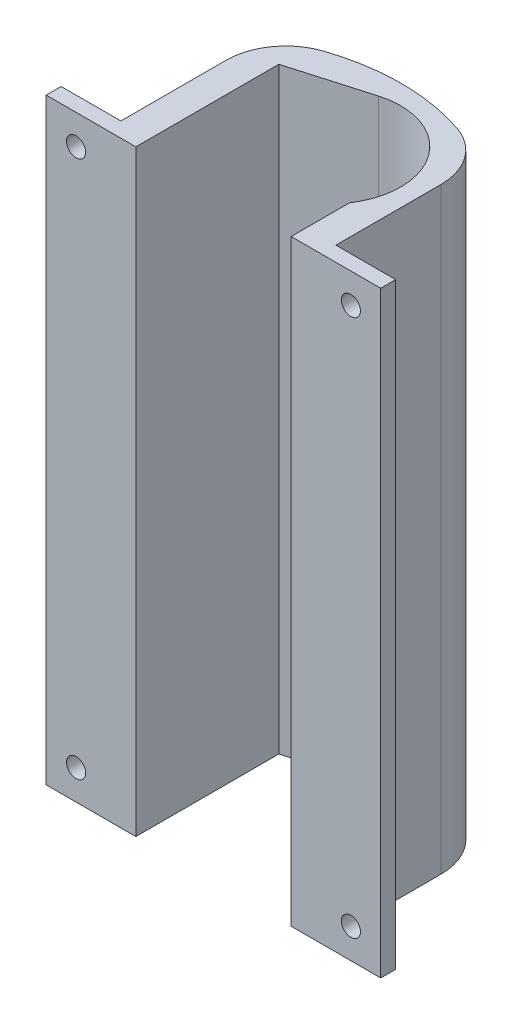
SolidWorks part; units mm, degrees
ref_plane "Front Plane" through (0, 0, 0) normal (0, 0, 1) x (1, 0, 0)
ref_plane "Top Plane" through (0, 0, 0) normal (0, 1, 0) x (1, 0, 0)
ref_plane "Right Plane" through (0, 0, 0) normal (1, 0, 0) x (0, 0, -1)
sketch "Sketch1" plane through (0, 0, 0) normal (0, 1, 0) x (1, 0, 0)
  line L0 (-20.574, -9.6521) -> (-4.162, -14.3967) construction
  line L1 (-4.1621, 14.3967) -> (-20.574, 9.652) construction
  line L2 (-20.574, 9.652) -> (-20.574, -9.6521) construction
  line L3 (-39.624, 20.7467) -> (-20.574, 20.7467) construction
  line L4 (-39.624, 20.7467) -> (-39.624, 17.5717) construction
  line L6 (12.446, 20.7467) -> (31.496, 20.7467) construction
  line L7 (-39.624, 17.5717) -> (-26.924, 17.5717) construction
  line L9 (-26.924, 17.5717) -> (-26.924, -12.8271) construction
  line L10 (31.496, 20.7467) -> (31.496, 17.5717) construction
  line L11 (31.496, 17.5717) -> (18.796, 17.5717) construction
  line L12 (18.796, 17.5717) -> (18.796, -12.8271) construction
  line L13 (-20.574, 9.652) -> (-20.574, 20.7467) construction
  line L14 (12.446, 20.7467) -> (12.446, 8.3478) construction
  line L15 (-69.4628, -37.4601) -> (67.1627, -37.4601) construction
  line L16 (-4.1621, -89.3169) -> (-20.574, -84.5722) construction
  line L17 (12.446, -95.6669) -> (12.446, -83.268)
  line L18 (-20.574, -84.5722) -> (-20.574, -95.6669)
  line L19 (18.796, -92.4919) -> (18.796, -62.0931)
  line L20 (31.496, -92.4919) -> (18.796, -92.4919)
  line L21 (31.496, -95.6669) -> (31.496, -92.4919)
  line L22 (-26.924, -92.4919) -> (-26.924, -62.0931)
  line L23 (-39.624, -92.4919) -> (-26.924, -92.4919)
  line L24 (12.446, -95.6669) -> (31.496, -95.6669)
  line L25 (-39.624, -95.6669) -> (-39.624, -92.4919)
  line L26 (-39.624, -95.6669) -> (-20.574, -95.6669)
  line L27 (-20.574, -84.5722) -> (-20.574, -65.2681)
  line L28 (-20.574, -65.2681) -> (-4.162, -60.5234)
  arc A0 (-4.162, -14.3967) -> (12.446, 8.3478) centre (0, 0) ccw construction
  arc A1 (-26.924, -12.8271) -> (18.796, -12.8271) centre (-4.064, 25.294) ccw construction
  arc A2 (12.446, 8.3478) -> (-4.1621, 14.3967) centre (0, 0) ccw construction
  arc A3 (12.446, -83.268) -> (-4.1621, -89.3169) centre (0, -74.9202) cw construction
  arc A4 (-26.924, -62.0931) -> (18.796, -62.0931) centre (-4.064, -100.2142) cw
  arc A5 (-4.162, -60.5234) -> (12.446, -83.268) centre (0, -74.9202) cw
  point P6 (12.446, 14.5473)
  dimension "D2" = 14.9863
  dimension "D14" = 37.4601
  dimension "D10" = 44.45
  dimension "D1" = 19.3041
  dimension "D3" = 16.4119
  dimension "D4" = 106.124
  dimension "D5" = 20.574
  dimension "D6" = 106.125
  dimension "D7" = 6.35
  dimension "D8" = 6.35
  dimension "D9" = 3.175
  dimension "D11" = 12.7
  dimension "D12" = 3.175
  dimension "D13" = 33.02
  dimension "D15" = 6.35
extrude "Boss-Extrude1" add sketch "Sketch1" along normal blind 127
fillet "Fillet2" radius 12.7 2 edges at (18.796, 63.5, 62.0931) (-26.924, 63.5, 62.0931)
sketch "Sketch2" plane through (0, 0, 92.4919) normal (0, 0, -1) x (-1, 0, 0)
  line L0 (-31.496, 0) -> (-18.796, 0) construction
  line L2 (39.624, 127) -> (39.624, 0) construction
  line L3 (-31.496, 127) -> (-18.796, 127) construction
  circle A0 centre (-25.146, 120.65) radius 2.032
  circle A1 centre (-25.146, 6.35) radius 2.032
  circle A2 centre (33.274, 120.65) radius 2.032
  circle A3 centre (33.274, 6.35) radius 2.032
  dimension "D1" = 4.064
  dimension "D2" = 6.35
  dimension "D3" = 6.35
  dimension "D4" = 6.35
  dimension "D5" = 6.35
extrude "Cut-Extrude1" cut sketch "Sketch2" against normal through all
